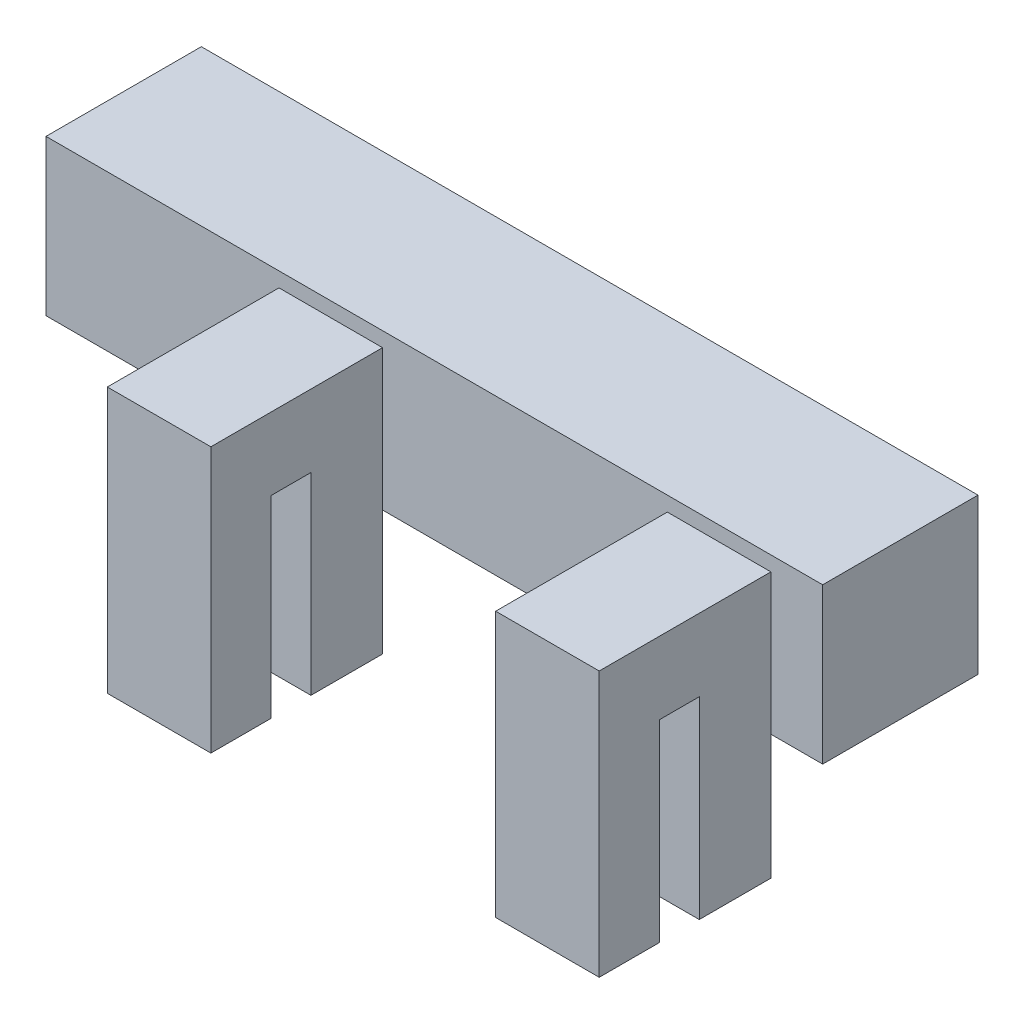
SolidWorks part; units mm, degrees
ref_plane "Front" through (0, 0, 0) normal (0, 0, 1) x (1, 0, 0)
ref_plane "Top" through (0, 0, 0) normal (0, 1, 0) x (1, 0, 0)
ref_plane "Right" through (0, 0, 0) normal (1, 0, 0) x (0, 0, -1)
sketch "Esquisse1" plane through (0, 0, 0) normal (0, 0, 1) x (1, 0, 0)
  line L1 (0, 0) -> (-150, 0)
  line L2 (0, 0) -> (0, 30)
  line L3 (0, 30) -> (-150, 30)
  line L4 (-150, 0) -> (-150, 30)
  dimension "D1" = 150
  dimension "D2" = 30
extrude "Boss.-Extru.1" add sketch "Esquisse1" along normal blind 30
sketch "Esquisse2" plane through (-150, 0, 0) normal (-1, 0, 0) x (0, 0, 1)
  line L0 (30, 30) -> (30, 0) construction
  line L1 (30, 27.1582) -> (63.1562, 27.1582)
  line L2 (30, 27.1582) -> (30, -24.0798)
  line L3 (30, -24.0798) -> (43.8334, -24.0798)
  line L4 (63.1562, 27.1582) -> (63.1562, -24.0798)
  line L5 (51.5046, -24.0798) -> (63.1562, -24.0798)
  line L7 (43.8334, -24.0798) -> (43.8334, 13.1907)
  line L8 (43.8334, 13.1907) -> (51.5046, 13.1907)
  line L9 (51.5046, -24.0798) -> (51.5046, 13.1907)
extrude "Boss.-Extru.2" add sketch "Esquisse2" against normal blind 20 from offset 45 offset against normal yes
pattern_linear "Répétition linéaire1" count 2 spacing 75 along (1, 0, 0) of "Boss.-Extru.2"
